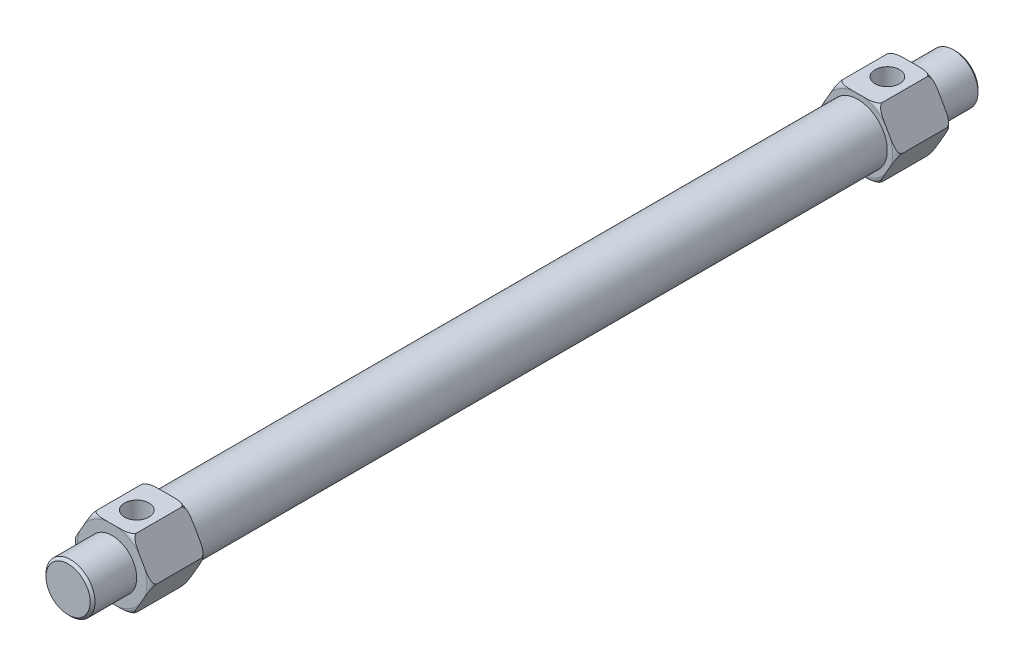
SolidWorks part; units mm, degrees
ref_plane "FRONT" through (0, 0, 0) normal (0, 0, 1) x (1, 0, 0)
ref_plane "TOP" through (0, 0, 0) normal (0, 1, 0) x (1, 0, 0)
ref_plane "RIGHT" through (0, 0, 0) normal (1, 0, 0) x (0, 0, -1)
ref_plane "FrontExtrusion" through (0, 0, 70.5) normal (0, 0, 1) x (1, 0, 0)
ref_plane "RearExtrusion" through (0, 0, -70.5) normal (0, 0, 1) x (1, 0, 0)
sketch "Sketch1" plane through (0, 0, 0) normal (0, 0, 1) x (1, 0, 0)
  circle A0 centre (0, 0) radius 6
  dimension "D1" = 12
extrude "Base-Extrude" add sketch "Sketch1" along normal up to surface (70.5 mm away) and the other way up to surface (70.5 mm away) up to plane "FrontExtrusion" other way up to plane "RearExtrusion"
sketch "Sketch7" plane through (0, 0, 0) normal (1, 0, 0) x (0, 0, -1)
  line L0 (-70.5, 6) -> (-70.5, 0)
  line L1 (-70.5, 50) -> (-70.5, -50) construction
  line L4 (-70.5, 0) -> (-90.5, 0)
  line L5 (-90.5, 0) -> (-90.5, 4.5)
  line L6 (-90, 5) -> (-71.5, 5)
  line L7 (0, 0) -> (-76.6329, 0) construction
  line L8 (-70.5, 0) -> (70.5, 0) construction
  line L10 (-70.5, 6) -> (-70.5, -6) construction
  line L11 (-90.5, 4.5) -> (-90, 5)
  line L12 (-70.5, 6) -> (-71.5, 5)
  line L13 (70.5, 6) -> (-70.5, 6) construction
  point P7 (-90.5, 5)
  dimension "D2" = 20
  dimension "D3" = 10
  dimension "D6" = 45
revolve "HeadCover" add sketch "Sketch7" angle 360 about L7
sketch "Sketch2" plane through (0, 0, 70.5) normal (0, 0, 1) x (1, 0, 0)
  line L1 (8.0829, 0) -> (4.0415, 7)
  line L2 (4.0415, 7) -> (-4.0415, 7)
  line L3 (-4.0415, 7) -> (-8.0829, 0)
  line L4 (-8.0829, 0) -> (-4.0415, -7)
  line L5 (-4.0415, -7) -> (4.0415, -7)
  line L6 (4.0415, -7) -> (8.0829, 0)
  circle A0 centre (0, 0) radius 7 construction
  dimension "D1" = 14
extrude "HeadCoverHex" add sketch "Sketch2" along normal blind 11
sketch "Sketch3" plane through (0, 0, 70.5) normal (0, 0, 1) x (1, 0, 0)
  circle A2 centre (0, 0) radius 14
  dimension "D1" = 28
extrude "HeadCoverRound" [suppressed] add sketch "Sketch3" along normal blind 11
ref_plane "PortPlane" through (0, 7, 0) normal (0, 1, 0) x (-1, 0, 0)
sketch "Sketch8" plane through (0, 7, 0) normal (0, 1, 0) x (-1, 0, 0)
  line L0 (0, 70.5) -> (0, -70.5) construction
  line L1 (4.5, 90.5) -> (-4.5, 90.5) construction
  circle A0 centre (0, 76.5) radius 2.5
  dimension "D1" = 5
  dimension "D2" = 14
extrude "Port" cut sketch "Sketch8" against normal up to surface (7 mm away)
sketch "Sketch9" plane through (0, 0, 0) normal (0, 1, 0) x (0, 0, -1)
  line L0 (-81.5, 8.0829) -> (-81.5, 7.0829)
  line L2 (-81.5, 8.0829) -> (-80.5, 8.0829)
  line L4 (-76, 12.4177) -> (-76, -8.0829) construction
  line L5 (-81.5, -8.0829) -> (-70.5, -8.0829) construction
  line L6 (-70.5, 8.0829) -> (-71.5, 8.0829)
  line L7 (-70.5, 8.0829) -> (-70.5, 7.0829)
  line L9 (0, 0) -> (-77.6243, 0) construction
  line L10 (-70.5, 0) -> (70.5, 0) construction
  line L11 (-81.5, 4.0415) -> (-81.5, 8.0829) construction
  line L12 (-81.5, 8.0829) -> (-70.5, 8.0829) construction
  arc A0 (-81.5, 7.0829) -> (-80.5, 8.0829) centre (-80.5, 7.0829) cw
  arc A1 (-70.5, 7.0829) -> (-71.5, 8.0829) centre (-71.5, 7.0829) ccw
  dimension "D1" = 1
revolve "HexRound" cut sketch "Sketch9" angle 360 about L9
chamfer "CoverChamfer" [suppressed] distance 0.5 angle 45
sketch "Sketch10" [suppressed] plane through (0, 0, 80.5) normal (0, 0, 1) x (1, 0, 0)
  line L0 (27.5, 9.5163) -> (27.5, -9.5163)
  line L1 (-27.5, 9.5163) -> (-27.5, -9.5163)
  circle A0 centre (0, 0) radius 29.1 construction
  arc A1 (-27.5, 9.5163) -> (-27.5, -9.5163) centre (0, 0) ccw
  arc A2 (27.5, -9.5163) -> (27.5, 9.5163) centre (0, 0) ccw
  dimension "D1" = 14
extrude "WrenchFlats" [suppressed] cut sketch "Sketch10" against normal through all
sketch "Sketch12" [suppressed] plane through (0, 0, 80.5) normal (0, 0, 1) x (1, 0, 0)
  line L0 (0, 0) -> (0, 11.2999) construction
  line L1 (0, 0) -> (0, 29.1) construction
  line L2 (0, 0) -> (8.3355, 0) construction
  line L3 (-16, 16) -> (16, 16) construction
  line L4 (16, 16) -> (16, -16) construction
  circle A0 centre (-16, 16) radius 4
  circle A1 centre (16, 16) radius 4
  circle A2 centre (-16, -16) radius 4
  circle A3 centre (16, -16) radius 4
  dimension "D1" = 30
  dimension "D2" = 8
extrude "FrontMounts" [suppressed] cut sketch "Sketch12" against normal blind 16
mirror "RoundCoverMirror" [suppressed] about plane through (0, 0, 0) normal (0, 0, 1)
mirror "HexCoverMirror" about plane through (0, 0, 0) normal (0, 0, 1) of "HeadCover", "HeadCoverHex", "HexRound", "Port"
sketch "Sketch11" [suppressed] plane through (27.5, 0, 0) normal (1, 0, 0) x (0, 0, -1)
  line L0 (0, 0) -> (0, 33.0566) construction
  line L1 (-80.5, 28.1) -> (-80.5, -28.1) construction
  circle A0 centre (-66.5, 0) radius 6
  circle A1 centre (66.5, 0) radius 6
  dimension "D1" = 12
  dimension "D2" = 14
extrude "CoverMounts" [suppressed] cut sketch "Sketch11" against normal blind 7.5
mirror "MountMirror" [suppressed] about plane through (0, 0, 0) normal (1, 0, 0)
mirror "FrontMountMirror" [suppressed] about plane through (0, 0, 0) normal (0, 0, 1)
sketch "Sketch13" [suppressed] plane through (0, 0, 95.5) normal (0, 0, 1) x (1, 0, 0)
  line L0 (-27.5, -5.7758) -> (-27.5, 5.7758) construction
  line L1 (-27.5, 29.1) -> (27.5, 29.1)
  line L2 (-27.5, 29.1) -> (-27.5, 27.5)
  line L3 (-27.5, 27.5) -> (27.5, 27.5)
  line L4 (27.5, 29.1) -> (27.5, 27.5)
  line L5 (27.5, 5.7758) -> (27.5, -5.7758) construction
  arc A0 (27.5, 9.5163) -> (-27.5, 9.5163) centre (0, 0) ccw construction
  dimension "D1" = 12
extrude "Head cover flat" [suppressed] cut sketch "Sketch13" against normal through all
